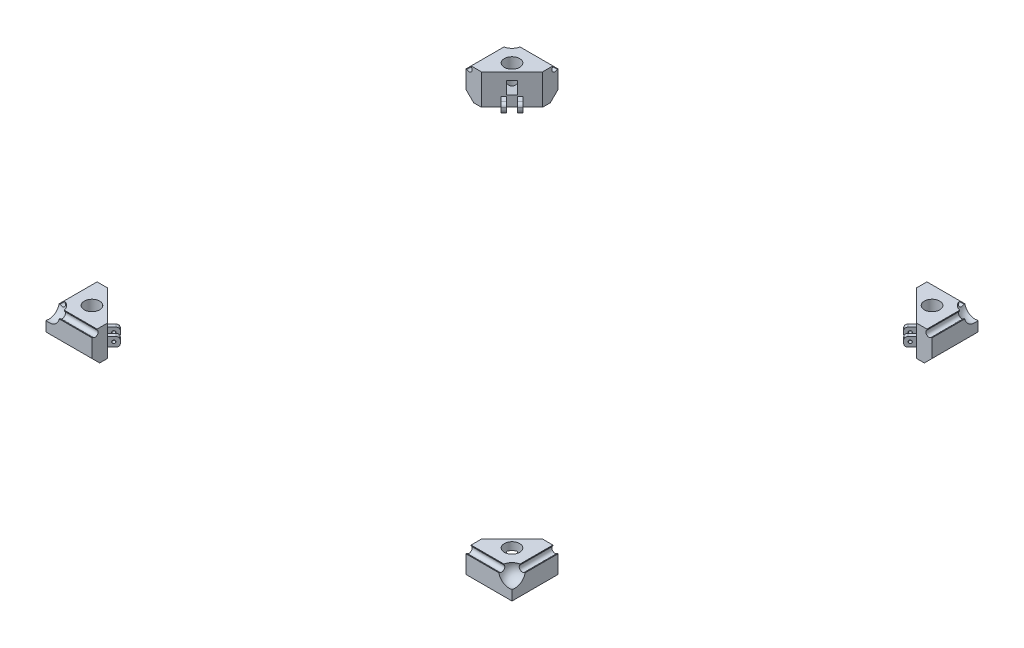
SolidWorks part; units mm, degrees
ref_plane "前基準面" through (0, 0, 0) normal (0, 0, 1) x (1, 0, 0)
ref_plane "上基準面" through (0, 0, 0) normal (0, 1, 0) x (1, 0, 0)
ref_plane "右基準面" through (0, 0, 0) normal (1, 0, 0) x (0, 0, -1)
sketch "草圖1" plane through (0, 0, 0) normal (0, 1, 0) x (1, 0, 0)
  line L0 (0, 0) -> (0, -30)
  line L1 (10, -30) -> (30, -10)
  line L2 (30, 0) -> (0, 0)
  line L3 (0, -30) -> (10, -30)
  line L4 (30, 0) -> (30, -10)
  circle A0 centre (15, -15) radius 5
  dimension "D4" = 10
  dimension "D1" = 30
  dimension "D2" = 15
  dimension "D3" = 15
  dimension "D5" = 10
extrude "填料-伸長1" add sketch "草圖1" along normal blind 20
sketch "草圖2" plane through (0, 0, 0) normal (0, 0, -1) x (-1, 0, 0)
  line L0 (-3.3229, 19.5) -> (-3.3229, 20)
  line L1 (-30, 20) -> (0, 20) construction
  line L2 (-3.3229, 20) -> (0, 20)
  line L3 (0, 20) -> (0, 16.6771)
  line L4 (0, 20) -> (0, 0) construction
  line L5 (0, 16.6771) -> (-0.5, 16.6771)
  arc A0 (-3.3229, 19.5) -> (-0.5, 16.6771) centre (-2, 18) ccw
  dimension "D3" = 2
  dimension "D1" = 2
  dimension "D2" = 2
  dimension "D4" = 0.5
extrude "除料-伸長1" cut sketch "草圖2" against normal through all
ref_plane "平面1" through (0, 0, 0) normal (-0.7071, 0, 0.7071) x (0.7071, 0, 0.7071)
mirror "鏡射1" about plane through (0, 0, 0) normal (-0.7071, 0, 0.7071) of "除料-伸長1"
ref_plane "平面4" through (0, 18, 0) normal (0, 1, 0) x (1, 0, 0)
sketch "草圖3" plane through (0, 18, 0) normal (0, 1, 0) x (1, 0, 0)
  line L0 (-38.8909, 38.8909) -> (38.8909, -38.8909) construction
  line L1 (0.5, -3.5) -> (2, -2) construction
  line L2 (9, -2) -> (-5, -2)
  arc A0 (9, -2) -> (-5, -2) centre (2, -2) ccw
  point P7 (2, -2)
  dimension "D1" = 7
revolve "除料-旋轉1" cut sketch "草圖3" angle 360 about L2
chamfer "導角1" distance 5 angle 45 2 edges at (15, 0, 0) (0, 0, 15)
sketch "草圖5" plane through (0, 0, 0) normal (-0.7071, 0, 0.7071) x (0.7071, 0, 0.7071)
  line L0 (25.2843, 15) -> (28.2843, 15)
  line L1 (28.2843, 20) -> (28.2843, 0) construction
  line L2 (28.2843, 15) -> (28.2843, 7)
  line L3 (28.2843, 7) -> (25.2843, 12)
  line L4 (25.2843, 12) -> (25.2843, 15)
  line L5 (23.5628, 20) -> (28.2843, 20) construction
  dimension "D1" = 5
  dimension "D2" = 8
  dimension "D3" = 3
  dimension "D4" = 3
extrude "除料-伸長2" cut sketch "草圖5" against normal mid plane 5
sketch "草圖6" plane through (0, 0, 0) normal (-0.7071, 0, 0.7071) x (0.7071, 0, 0.7071)
  line L0 (28.2843, 3) -> (34.2843, 3) construction
  line L1 (28.2843, 0) -> (32.2843, 0)
  line L2 (28.2843, 0) -> (28.2843, 6)
  line L3 (28.2843, 6) -> (32.2843, 6)
  line L4 (34.2843, 2) -> (34.2843, 4)
  arc A0 (32.2843, 6) -> (34.2843, 4) centre (32.2843, 4) cw
  arc A1 (32.2843, 0) -> (34.2843, 2) centre (32.2843, 2) ccw
  circle A2 centre (31.2843, 3) radius 1
  point P12 (34.2843, 3)
  dimension "D1" = 2
  dimension "D2" = 2
  dimension "D5" = 2
  dimension "D3" = 6
  dimension "D4" = 6
extrude "填料-伸長2" add sketch "草圖6" along normal mid plane 10
sketch "草圖7" plane through (0, 6, 0) normal (0, 1, 0) x (1, 0, 0)
  line L0 (22.4749, -26.0104) -> (18.2322, -21.7678)
  line L1 (22.4749, -26.0104) -> (26.0104, -22.4749)
  line L2 (18.2322, -21.7678) -> (21.7678, -18.2322)
  line L3 (26.0104, -22.4749) -> (21.7678, -18.2322)
  line L4 (22.4749, -26.0104) -> (21.7678, -18.2322) construction
  line L5 (18.2322, -21.7678) -> (26.0104, -22.4749) construction
  line L6 (20.7071, -27.7782) -> (27.7782, -20.7071) construction
  line L7 (16.4645, -23.5355) -> (23.5355, -16.4645) construction
  line L8 (-38.8909, 38.8909) -> (38.8909, -38.8909) construction
  point P1 (22.1213, -22.1213)
  point P9 (0, 0)
  dimension "D1" = 5
extrude "除料-伸長3" cut sketch "草圖7" against normal through all both and the other way through all
ref_plane "平面2" through (152, 0, 0) normal (1, 0, 0) x (0, 0, -1)
mirror "鏡射3" about plane through (152, 0, 0) normal (1, 0, 0) of bodies 110 103
ref_plane "平面3" through (0, 0, 152) normal (0, 0, 1) x (1, 0, 0)
mirror "鏡射4" about plane through (0, 0, 152) normal (0, 0, 1) of bodies 104 110 103
